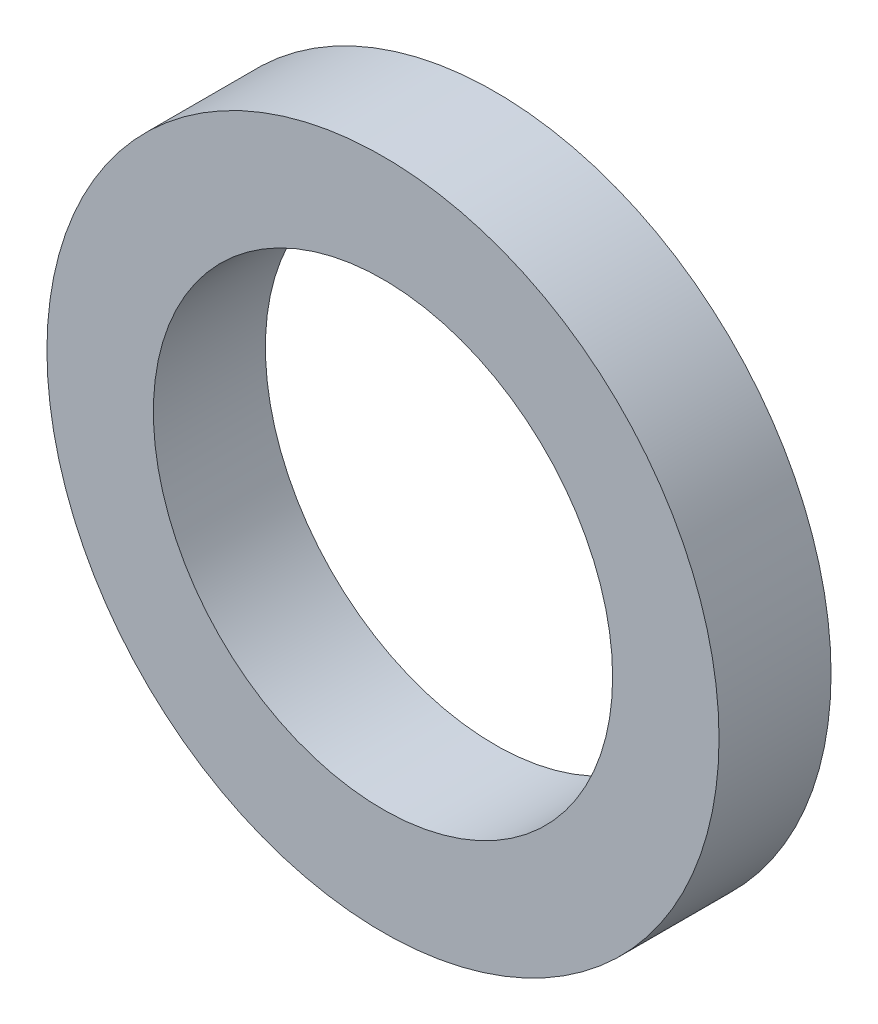
SolidWorks part; units mm, degrees
ref_plane "Front Plane" through (0, 0, 0) normal (0, 0, 1) x (1, 0, 0)
ref_plane "Top Plane" through (0, 0, 0) normal (0, 1, 0) x (1, 0, 0)
ref_plane "Right Plane" through (0, 0, 0) normal (1, 0, 0) x (0, 0, -1)
sketch "Sketch1" plane through (0, 0, 0) normal (0, 0, 1) x (1, 0, 0)
  line L3 (0, 0) -> (0, 6) construction
  circle A0 centre (0, 0) radius 4.1
  circle A1 centre (0, 0) radius 6
  dimension "D1" = 8.2
  dimension "D2" = 12
extrude "Boss-Extrude1" add sketch "Sketch1" along normal blind 2
